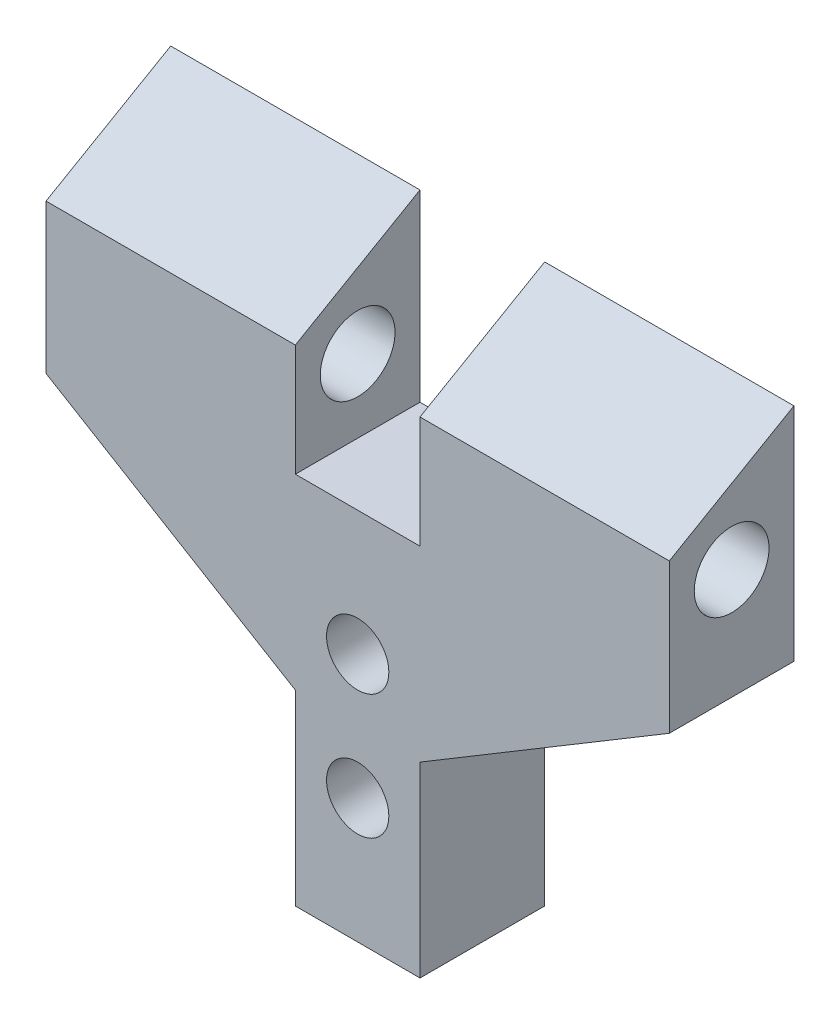
SolidWorks part; units mm, degrees
ref_plane "Plan de face" through (0, 0, 0) normal (0, 0, 1) x (1, 0, 0)
ref_plane "Plan de dessus" through (0, 0, 0) normal (0, 1, 0) x (1, 0, 0)
ref_plane "Plan de droite" through (0, 0, 0) normal (1, 0, 0) x (0, 0, -1)
sketch "Esquisse1" plane through (0, 0, 0) normal (0, 0, 1) x (1, 0, 0)
  line L0 (-25, 12) -> (-5, 0)
  line L1 (-5, -15) -> (5, -15)
  line L2 (-5, -15) -> (-5, 0)
  line L3 (-5, 15) -> (5, 15)
  line L4 (5, -15) -> (5, 0)
  line L5 (-5, -15) -> (5, 15) construction
  line L6 (-5, 15) -> (5, -15) construction
  line L8 (-5, 15) -> (-5, 29.75)
  line L9 (-5, 29.75) -> (-25, 29.75)
  line L10 (-25, 12) -> (-25, 29.75)
  line L12 (5, 15) -> (5, 29.75)
  line L13 (5, 29.75) -> (25, 29.75)
  line L14 (25, 12) -> (25, 29.75)
  line L15 (5, 0) -> (25, 12)
  circle A0 centre (0, -5) radius 2.5
  circle A1 centre (0, 5) radius 2.5
  point P0 (0, 3.5555)
  dimension "D3" = 10
  dimension "D4" = 5
  dimension "D11" = 5
  dimension "D1" = 30
  dimension "D2" = 10
  dimension "D5" = 5
  dimension "D8" = 17.75
  dimension "D9" = 17.75
extrude "Boss.-Extru.1" add sketch "Esquisse1" along normal blind 10
sketch "Esquisse2" plane through (-25, 0, 0) normal (-1, 0, 0) x (0, 0, 1)
  line L0 (0, 29.75) -> (10, 29.75)
  line L1 (10, 29.75) -> (10, 23.9765)
  line L2 (10, 12) -> (10, 29.75) construction
  line L3 (10, 23.9765) -> (0, 29.75)
  line L4 (0, 29.75) -> (10, 12) construction
  line L5 (10, 12) -> (10, 20.875) construction
  line L6 (10, 20.875) -> (5, 20.875) construction
  circle A0 centre (5, 20.875) radius 3
  dimension "D2" = 6
  dimension "D1" = 30
extrude "Enlèv. mat.-Extru.1" cut sketch "Esquisse2" against normal up to surface (50 mm away) up to face at (25, 20.875, 5)
